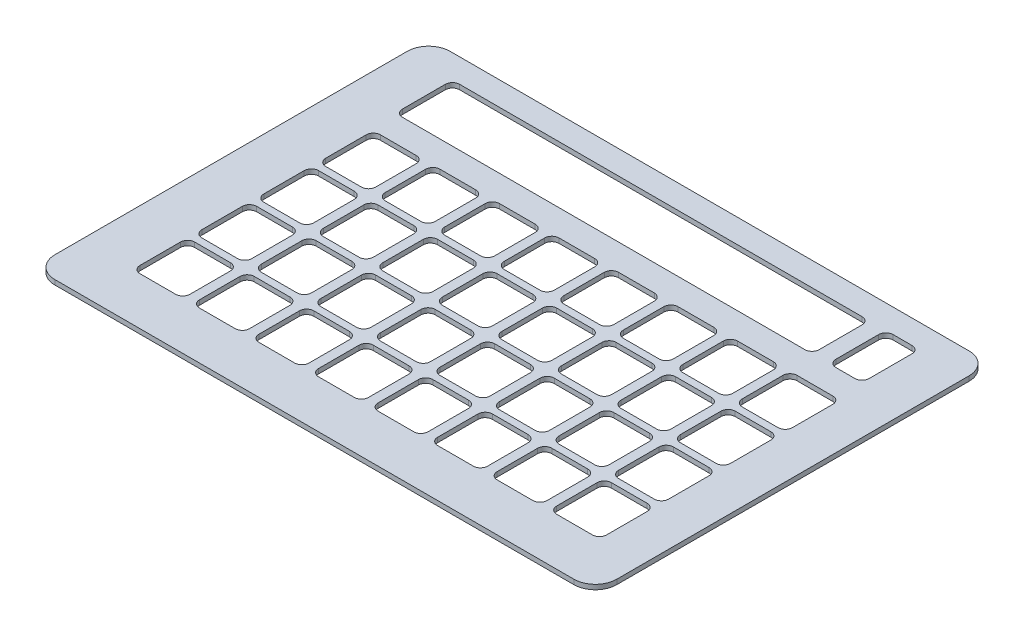
SolidWorks part; units mm, degrees
ref_plane "Front Plane" through (0, 0, 0) normal (0, 0, 1) x (1, 0, 0)
ref_plane "Top Plane" through (0, 0, 0) normal (0, 1, 0) x (1, 0, 0)
ref_plane "Right Plane" through (0, 0, 0) normal (1, 0, 0) x (0, 0, -1)
sketch "Sketch1" plane through (0, 0, 0) normal (0, 1, 0) x (1, 0, 0)
  line L1 (-118, -83) -> (118, -83)
  line L2 (-118, -83) -> (-118, 83)
  line L3 (-118, 83) -> (118, 83)
  line L4 (118, -83) -> (118, 83)
  line L5 (-118, -83) -> (118, 83) construction
  line L6 (-118, 83) -> (118, -83) construction
  point P0 (0, 0)
  dimension "D1" = 236
  dimension "D2" = 166
extrude "Outer Profile" add sketch "Sketch1" along normal blind 1
sketch "Sketch2" plane through (0, 1, 0) normal (0, 1, 0) x (1, 0, 0)
  line L1 (-118, -83) -> (118, -83)
  line L2 (-118, -83) -> (-118, 83)
  line L3 (-118, 83) -> (118, 83)
  line L4 (118, -83) -> (118, 83)
  line L5 (-118, -83) -> (118, 83) construction
  line L6 (-118, 83) -> (118, -83) construction
  line L8 (118, 83) -> (-118, 83) construction
  line L9 (-118, 83) -> (-118, -83) construction
  point P0 (0, 0)
extrude "Inner Profile" add sketch "Sketch2" along normal blind 1
fillet "Fillet1" radius 9 4 edges at (118, 1, 83) (118, 1, -83) (-118, 1, -83) (-118, 1, 83)
sketch "Sketch3" plane through (0, 2, 0) normal (0, 1, 0) x (1, 0, 0)
  line L0 (0, 0) -> (0, -50000) construction
  line L1 (-98, -73) -> (98, -73) construction
  line L2 (-98, -73) -> (-98, 73) construction
  line L3 (-98, 73) -> (98, 73) construction
  line L4 (98, -73) -> (98, 73) construction
  line L5 (-98, -73) -> (98, 73) construction
  line L6 (-98, 73) -> (98, -73) construction
  line L8 (-93.25, -63) -> (-78.25, -63)
  line L9 (-96.25, -60) -> (-96.25, -43)
  line L10 (-93.25, -40) -> (-78.25, -40)
  line L11 (-75.25, -60) -> (-75.25, -43)
  line L12 (-96.25, -63) -> (-75.25, -40) construction
  line L13 (-96.25, -40) -> (-75.25, -63) construction
  arc A0 (-93.25, -63) -> (-96.25, -60) centre (-93.25, -60) cw
  arc A1 (-78.25, -63) -> (-75.25, -60) centre (-78.25, -60) ccw
  arc A2 (-78.25, -40) -> (-75.25, -43) centre (-78.25, -43) cw
  arc A3 (-96.25, -43) -> (-93.25, -40) centre (-93.25, -43) cw
  point P0 (0, 0)
  point P5 (-85.75, -51.5)
  dimension "D7" = 3
  dimension "D1" = 196
  dimension "D2" = 146
  dimension "D3" = 21
  dimension "D4" = 23
  dimension "D5" = 96.25
  dimension "D6" = 10
sketch "Sketch7" plane through (0, 2, 0) normal (0, 1, 0) x (1, 0, 0)
  line L1 (-98, -73) -> (98, -73)
  line L2 (-98, -73) -> (-98, 73)
  line L3 (-98, 73) -> (98, 73)
  line L4 (98, -73) -> (98, 73)
  line L5 (-98, -73) -> (98, 73) construction
  line L6 (-98, 73) -> (98, -73) construction
  point P0 (0, 0)
  dimension "D1" = 196
  dimension "D2" = 146
extrude "Cutout" cut sketch "Sketch3" against normal through all
pattern_linear "Cutouts" count 8 spacing 25 along (1, 0, 0) count 4 spacing 26 along (0, 0, -1) of "Cutout"
sketch "Sketch9" plane through (0, 2, 0) normal (0, 1, 0) x (1, 0, 0)
  line L0 (-118, 74) -> (-118, -74) construction
  line L3 (-95, 49) -> (74, 49)
  line L4 (-98, 52) -> (-98, 70)
  line L5 (-95, 73) -> (74, 73)
  line L6 (77, 52) -> (77, 70)
  line L7 (-98, 49) -> (77, 73) construction
  line L8 (-98, 73) -> (77, 49) construction
  line L9 (104.5, 83) -> (-104.5, 83) construction
  line L10 (87, 49) -> (95, 49)
  line L11 (84, 52) -> (84, 70)
  line L12 (87, 73) -> (95, 73)
  line L13 (98, 52) -> (98, 70)
  line L14 (84, 49) -> (98, 73) construction
  line L15 (84, 73) -> (98, 49) construction
  line L16 (118, 8) -> (118, 69.5) construction
  arc A0 (95, 73) -> (98, 70) centre (95, 70) cw
  arc A1 (95, 49) -> (98, 52) centre (95, 52) ccw
  arc A2 (87, 49) -> (84, 52) centre (87, 52) cw
  arc A3 (84, 70) -> (87, 73) centre (87, 70) cw
  arc A4 (74, 49) -> (77, 52) centre (74, 52) ccw
  arc A5 (74, 73) -> (77, 70) centre (74, 70) cw
  arc A6 (-95, 49) -> (-98, 52) centre (-95, 52) cw
  arc A7 (-98, 70) -> (-95, 73) centre (-95, 70) cw
  point P0 (91, 61)
  point P10 (-10.5, 61)
  dimension "D4" = 3
  dimension "D1" = 22
  dimension "D2" = 27
  dimension "D3" = 20
  dimension "D5" = 24
  dimension "D6" = 20
  dimension "D7" = 175
extrude "Top" cut sketch "Sketch9" against normal through all
